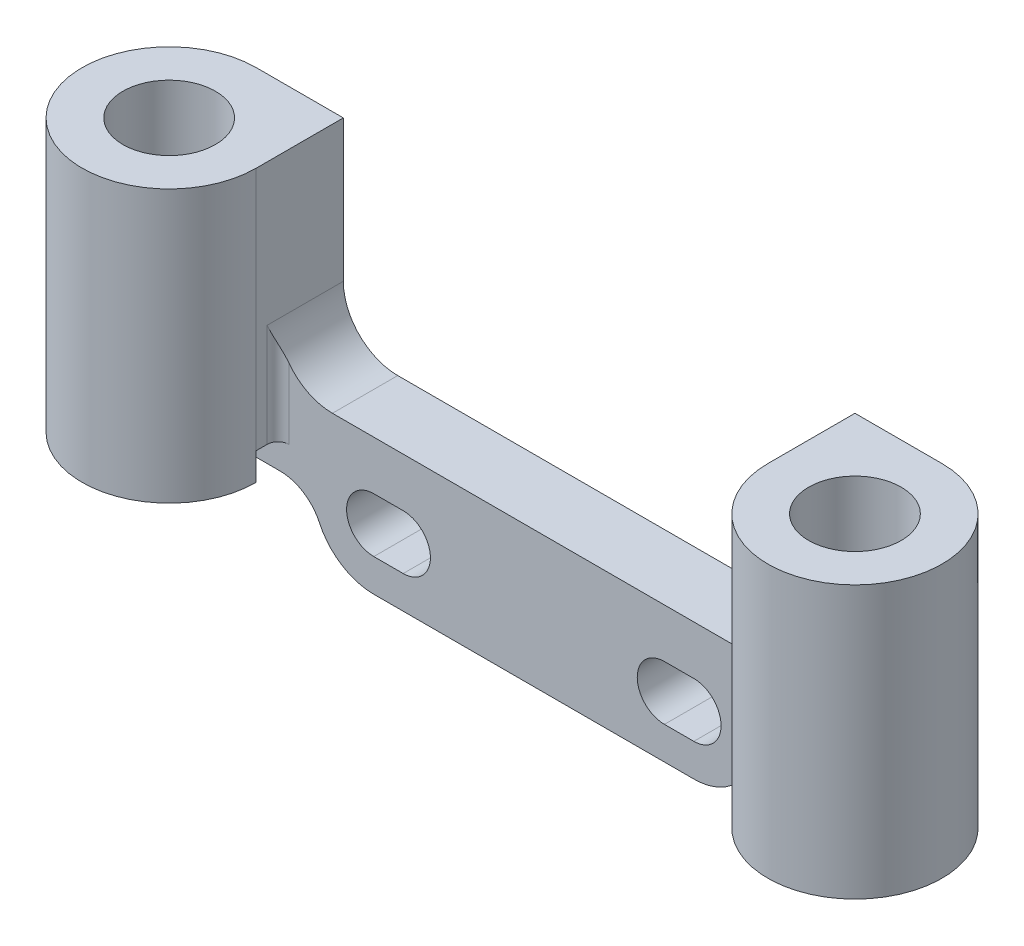
SolidWorks part; units mm, degrees
other "标注1"
sketch "草图10" plane through (-27.3, 30.5003, -0.0003) normal (-0.0004, 0.0683, -0.9977) x (-0.9714, 0.2371, 0.0166)
ref_plane "前视基准面" through (0, 0, 0) normal (0, 0, 1) x (1, 0, 0)
ref_plane "上视基准面" through (0, 0, 0) normal (0, 1, 0) x (1, 0, 0)
ref_plane "右视基准面" through (0, 0, 0) normal (1, 0, 0) x (0, 0, -1)
other "Configuration Table"
sketch "草图1" plane through (0, 0, 0) normal (0, 0, 1) x (1, 0, 0)
  line L0 (24.2, 3) -> (26.9, 3)
  line L1 (-2.5, 8) -> (0.2, 8)
  line L3 (-2.5, 3) -> (0.2, 3)
  line L5 (24.2, 8) -> (26.9, 8)
  line L11 (35.5168, 5.5) -> (51.7, 5.5)
  line L14 (-27.3, 5.5) -> (-11.1168, 5.5)
  line L18 (-11.3, 30.5) -> (-11.3, 17.5)
  line L19 (-6.3, 12.5) -> (30.7, 12.5)
  line L20 (35.7, 30.5) -> (35.7, 17.5)
  line L21 (-11.3, 30.5) -> (35.7, 30.5)
  line L22 (-27.3, 5.5) -> (-27.3, 0)
  line L23 (-27.3, 0) -> (-2.5, 0)
  line L24 (26.9, 0) -> (51.7, 0)
  line L25 (51.7, 0) -> (51.7, 5.5)
  arc A0 (0.2, 3) -> (0.2, 8) centre (0.2, 5.5) ccw
  arc A1 (24.2, 8) -> (24.2, 3) centre (24.2, 5.5) ccw
  arc A2 (-2.5, 8) -> (-2.5, 3) centre (-2.5, 5.5) ccw
  arc A3 (26.9, 3) -> (26.9, 8) centre (26.9, 5.5) ccw
  arc A4 (-7.4887, 3.1842) -> (-2.5, 0) centre (-2.5, 5.5) ccw
  arc A5 (26.9, 0) -> (31.8887, 3.1842) centre (26.9, 5.5) ccw
  arc A6 (30.7, 12.5) -> (35.7, 17.5) centre (30.7, 17.5) ccw
  arc A7 (-11.3, 17.5) -> (-6.3, 12.5) centre (-6.3, 17.5) ccw
  arc A8 (35.5168, 5.5) -> (31.8887, 3.1842) centre (35.5168, 1.5) ccw
  arc A9 (-7.4887, 3.1842) -> (-11.1168, 5.5) centre (-11.1168, 1.5) ccw
  point P31 (-11.3, 12.5)
  point P36 (-8, 5.5)
  dimension "D1" = 5
  dimension "D2" = 47
  dimension "D4" = 18
  dimension "D3" = 11
  dimension "D5" = 40.4
  dimension "D6" = 5
  dimension "D9" = 25
  dimension "D11" = 4
  dimension "D7" = 2.7
  dimension "D8" = 19.3
  dimension "D10" = 5.5
sketch "草图5" plane through (0, 0, 0) normal (0, 1, 0) x (1, 0, 0)
  line L0 (-19.3, 0) -> (43.7, 0)
  line L3 (-10.3, -6) -> (34.7, -6)
  line L7 (-11.3, -7) -> (-11.3, -8)
  line L11 (35.7, -7) -> (35.7, -8)
  arc A0 (-19.3, 0) -> (-11.3, -8) centre (-19.3, -8) ccw
  arc A1 (35.7, -8) -> (43.7, 0) centre (43.7, -8) ccw
  circle A6 centre (-19.3, -8) radius 4.25
  circle A7 centre (43.7, -8) radius 4.25
  arc A8 (-11.3, -7) -> (-10.3, -6) centre (-10.3, -7) cw
  arc A9 (34.7, -6) -> (35.7, -7) centre (34.7, -7) cw
  dimension "D1" = 16
  dimension "D2" = 8.5
  dimension "D3" = 1
  dimension "D4" = 1
extrude "凸台-拉伸5" add sketch "草图5" along normal blind 30.5
extrude "切除-拉伸2" cut sketch "草图1" along normal through all
sketch "草图9" plane through (0, 0, 0) normal (1, 0, 0) x (0, 0, -1)
  line L10 (-6, 5.4157) -> (-6, 3.1842) construction
  line L11 (-6, 5.0239) -> (-8, 5.0239)
  line L12 (-6, 5.0239) -> (-6, 8.0239)
  line L13 (-6, 8.0239) -> (-8, 8.0239)
  line L14 (-8, 5.0239) -> (-8, 8.0239)
  dimension "D1" = 2
  dimension "D2" = 3
extrude "切除-拉伸5" cut sketch "草图9" against normal blind 18 and the other way blind 42
